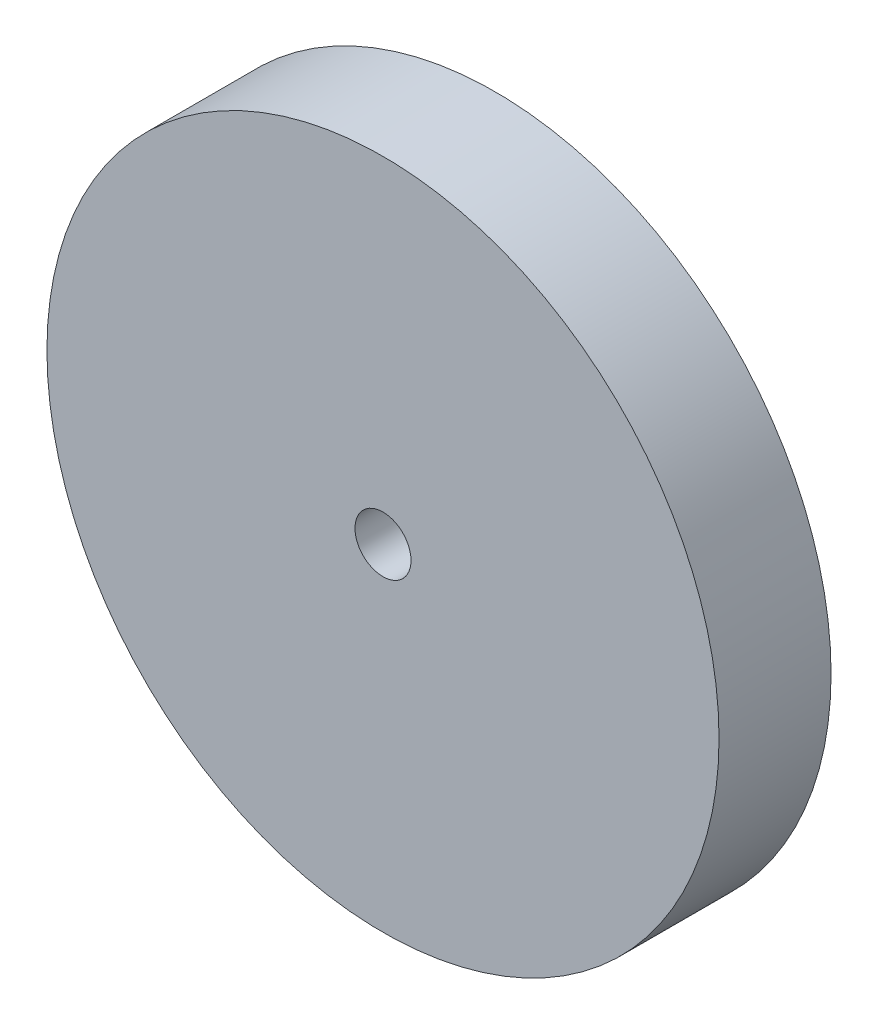
SolidWorks part; units mm, degrees
ref_plane "Front Plane" through (0, 0, 0) normal (0, 0, 1) x (1, 0, 0)
ref_plane "Top Plane" through (0, 0, 0) normal (0, 1, 0) x (1, 0, 0)
ref_plane "Right Plane" through (0, 0, 0) normal (1, 0, 0) x (0, 0, -1)
sketch "Sketch1" plane through (0, 0, 0) normal (0, 0, 1) x (1, 0, 0)
  circle A0 centre (0, 0) radius 38.1
  circle A1 centre (0, 0) radius 3.175
  dimension "D1" = 76.2
  dimension "D2" = 6.35
extrude "Boss-Extrude1" add sketch "Sketch1" along normal blind 12.7
